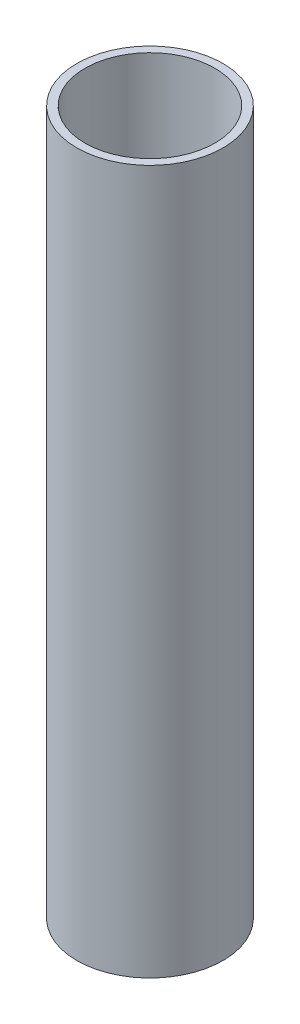
SolidWorks part; units mm, degrees
material "AISI 1020"
ref_plane "Front Plane" through (0, 0, 0) normal (0, 0, 1) x (1, 0, 0)
ref_plane "Top Plane" through (0, 0, 0) normal (0, 1, 0) x (1, 0, 0)
ref_plane "Right Plane" through (0, 0, 0) normal (1, 0, 0) x (0, 0, -1)
sketch "Sketch1" plane through (0, 0, 0) normal (0, 1, 0) x (1, 0, 0)
  circle A0 centre (13.6327, 6.0794) radius 7.0485
  circle A1 centre (13.6327, 6.0794) radius 7.9375
  dimension "D1" = 14.097
  dimension "D2" = 15.875
extrude "Boss-Extrude1" add sketch "Sketch1" along normal blind 76.4
